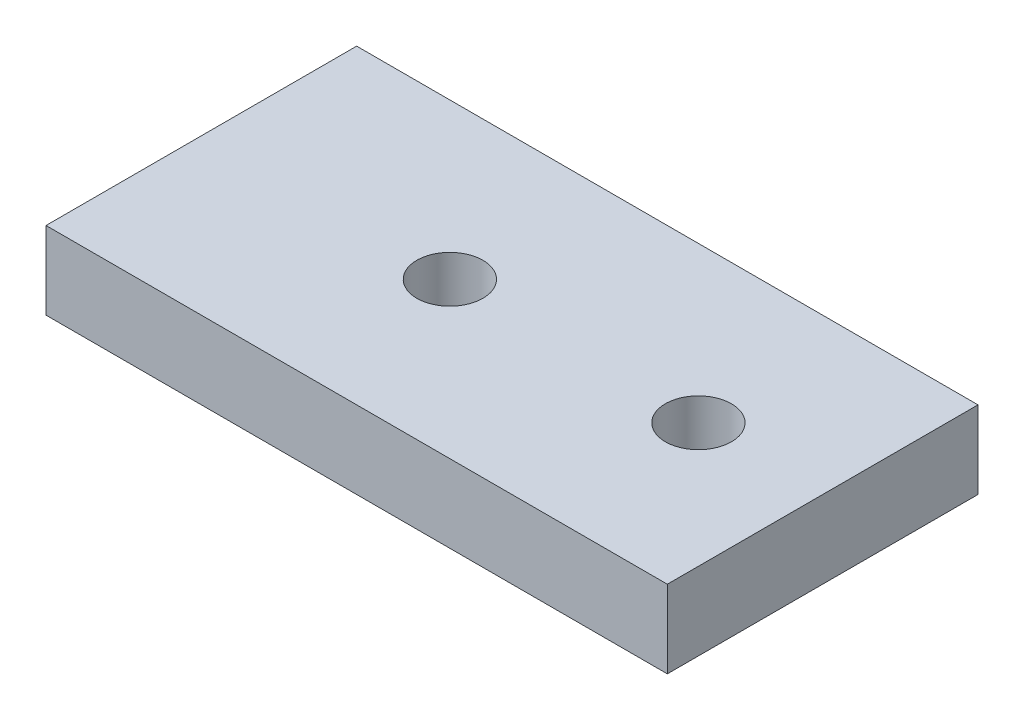
SolidWorks part; units mm, degrees
ref_plane "Front Plane" through (0, 0, 0) normal (0, 0, 1) x (1, 0, 0)
ref_plane "Top Plane" through (0, 0, 0) normal (0, 1, 0) x (1, 0, 0)
ref_plane "Right Plane" through (0, 0, 0) normal (1, 0, 0) x (0, 0, -1)
sketch "Sketch1" plane through (0, 0, 0) normal (0, 1, 0) x (1, 0, 0)
  line L1 (-20, -10) -> (20, -10)
  line L2 (-20, -10) -> (-20, 10)
  line L3 (-20, 10) -> (20, 10)
  line L4 (20, -10) -> (20, 10)
  line L5 (-20, -10) -> (20, 10) construction
  line L6 (-20, 10) -> (20, -10) construction
  line L7 (-20, 0) -> (20, 0) construction
  circle A2 centre (12, 0) radius 2.125
  circle A3 centre (-4, 0) radius 2.125
  point P0 (0, 0)
  dimension "D3" = 4.25
  dimension "D5" = 4.25
  dimension "D1" = 20
  dimension "D2" = 40
  dimension "D4" = 8
  dimension "D6" = 16
extrude "Boss-Extrude1" add sketch "Sketch1" along normal blind 5
